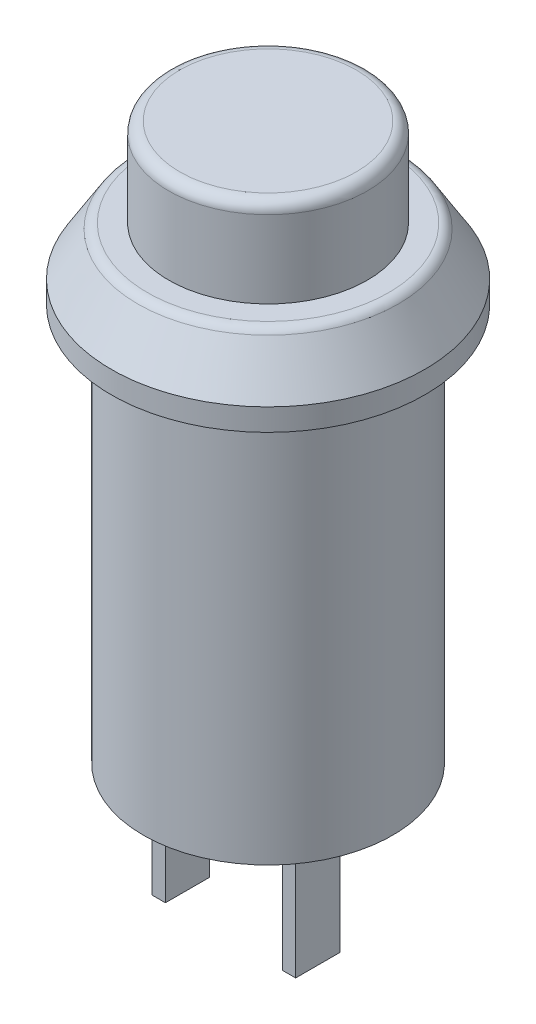
SolidWorks part; units mm, degrees
ref_plane "Front Plane" through (0, 0, 0) normal (0, 0, 1) x (1, 0, 0)
ref_plane "Top Plane" through (0, 0, 0) normal (0, 1, 0) x (1, 0, 0)
ref_plane "Right Plane" through (0, 0, 0) normal (1, 0, 0) x (0, 0, -1)
sketch "Sketch1" plane through (0, 0, 0) normal (0, 0, 1) x (1, 0, 0)
  line L0 (0, 0) -> (0, 30.0938) construction
  line L1 (0, 0) -> (-5.65, 0)
  line L2 (-5.65, 0) -> (-5.65, 18)
  line L3 (-5.65, 18) -> (-7.1, 18)
  line L4 (-7.1, 18) -> (-7.1, 19)
  line L5 (-4.5, 21.2) -> (-5.75, 21.2)
  line L6 (-5.75, 21.2) -> (-7.1, 19)
  line L7 (0, 0) -> (0, 25.2)
  line L8 (-4.5, 21.2) -> (-4.5, 25.2)
  line L9 (-4.5, 25.2) -> (0, 25.2)
  dimension "D1" = 18
  dimension "D2" = 11.3
  dimension "D3" = 14.2
  dimension "D4" = 1
  dimension "D5" = 11.5
  dimension "D6" = 2.2
  dimension "D7" = 9
  dimension "D8" = 4
revolve "Revolve1" add sketch "Sketch1" angle 360 about L0
fillet "Fillet1" radius 0.5 2 edges at (0, 25.2, -4.5) (0, 21.2, -5.75)
sketch "Sketch2" plane through (0, 0, 0) normal (0, -1, 0) x (1, 0, 0)
  line L0 (5.65, 0) -> (-5.65, 0) construction
  line L1 (0, 0) -> (0, 5.65) construction
  line L2 (-3.25, 2) -> (-2.65, 2)
  line L3 (3.25, 0) -> (2.65, 0)
  line L4 (3.25, 0) -> (3.25, 2)
  line L5 (3.25, 2) -> (2.65, 2)
  line L6 (2.65, 0) -> (2.65, 2)
  line L7 (-2.65, 0) -> (-2.65, 2)
  line L8 (-3.25, 0) -> (-3.25, 2)
  line L9 (-3.25, 0) -> (-2.65, 0)
  circle A0 centre (0, 0) radius 5.65 construction
  circle A1 centre (0, 0) radius 5.65 construction
  dimension "D1" = 2.65
  dimension "D2" = 0.6
  dimension "D3" = 2
extrude "Boss-Extrude1" add sketch "Sketch2" along normal blind 5.8
